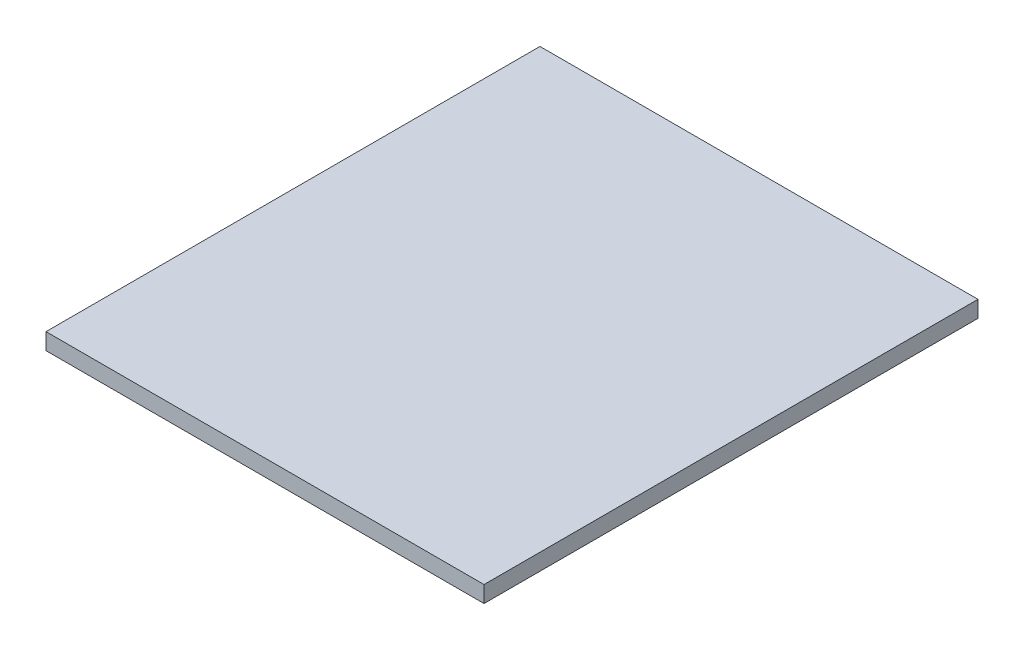
SolidWorks part; units mm, degrees
ref_plane "Front Plane" through (0, 0, 0) normal (0, 0, 1) x (1, 0, 0)
ref_plane "Top Plane" through (0, 0, 0) normal (0, 1, 0) x (1, 0, 0)
ref_plane "Right Plane" through (0, 0, 0) normal (1, 0, 0) x (0, 0, -1)
sketch "Sketch1" plane through (0.5973, 0, -0.0629) normal (0, 1, 0) x (1, 0, 0)
  line L1 (-33.3892, 18.7769) -> (56.8886, 18.7769)
  line L2 (-33.3892, 18.7769) -> (-33.3892, -83.0312)
  line L3 (-33.3892, -83.0312) -> (56.8886, -83.0312)
  line L4 (56.8886, 18.7769) -> (56.8886, -83.0312)
extrude "Boss-Extrude1" add sketch "Sketch1" along normal blind 0.5917 and the other way blind 2.806
